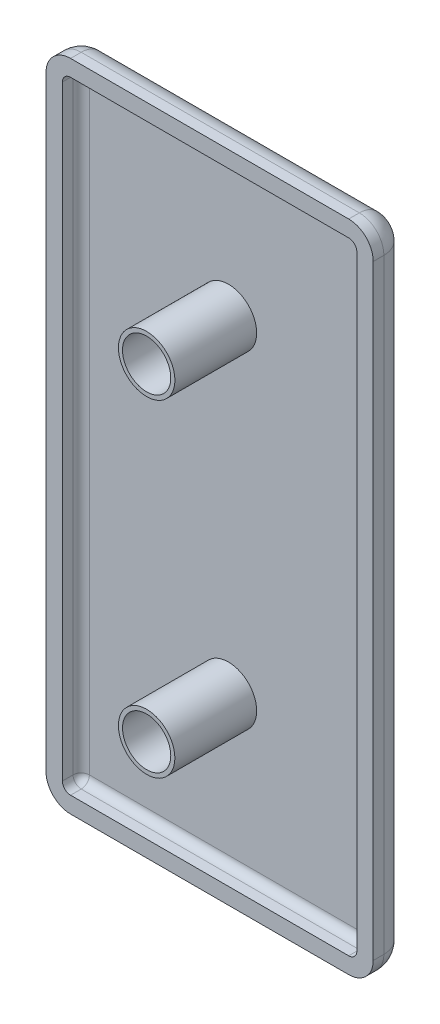
SolidWorks part; units mm, degrees
ref_plane "前视基准面" through (0, 0, 0) normal (0, 0, 1) x (1, 0, 0)
ref_plane "上视基准面" through (0, 0, 0) normal (0, 1, 0) x (1, 0, 0)
ref_plane "右视基准面" through (0, 0, 0) normal (1, 0, 0) x (0, 0, -1)
sketch "草图1" plane through (0, 0, 0) normal (0, 0, 1) x (1, 0, 0)
  line B0 (3, 0) -> (37, 0)
  line B1 (40, 3) -> (40, 77)
  line B2 (37, 80) -> (3, 80)
  line B3 (0, 77) -> (0, 3)
  arc B4 (37, 0) -> (40, 3) centre (37, 3) ccw
  arc B5 (40, 77) -> (37, 80) centre (37, 77) ccw
  arc B6 (3, 80) -> (0, 77) centre (3, 77) ccw
  arc B7 (0, 3) -> (3, 0) centre (3, 3) ccw
sketch_block_instance "A$C630572F7-1"
sketch_block "A$C630572F7"
extrude "凸台-拉伸1" add sketch "草图1" along normal blind 4.3
fillet "圆角1" radius 3 8 edges at (0.8787, 0.8787, 0) (0, 40, 0) (0.8787, 79.1213, 0) (20, 80, 0) (39.1213, 79.1213, 0) (40, 40, 0) (39.1213, 0.8787, 0) (20, 0, 0)
shell "抽壳1" thickness 2
sketch "草图3" plane through (0, 0, 2) normal (0, 0, 1) x (1, 0, 0)
  line L0 (2, 40) -> (26.5807, 40) construction
  line L1 (2, 77) -> (2, 3) construction
  circle A0 centre (20, 20) radius 3.45
  circle A1 centre (20, 20) radius 2.95
  circle A2 centre (20, 60) radius 2.95
  circle A3 centre (20, 60) radius 3.45
  dimension "D1" = 20
  dimension "D2" = 6.9
  dimension "D3" = 0.5
extrude "凸台-拉伸2" add sketch "草图3" along normal blind 10
